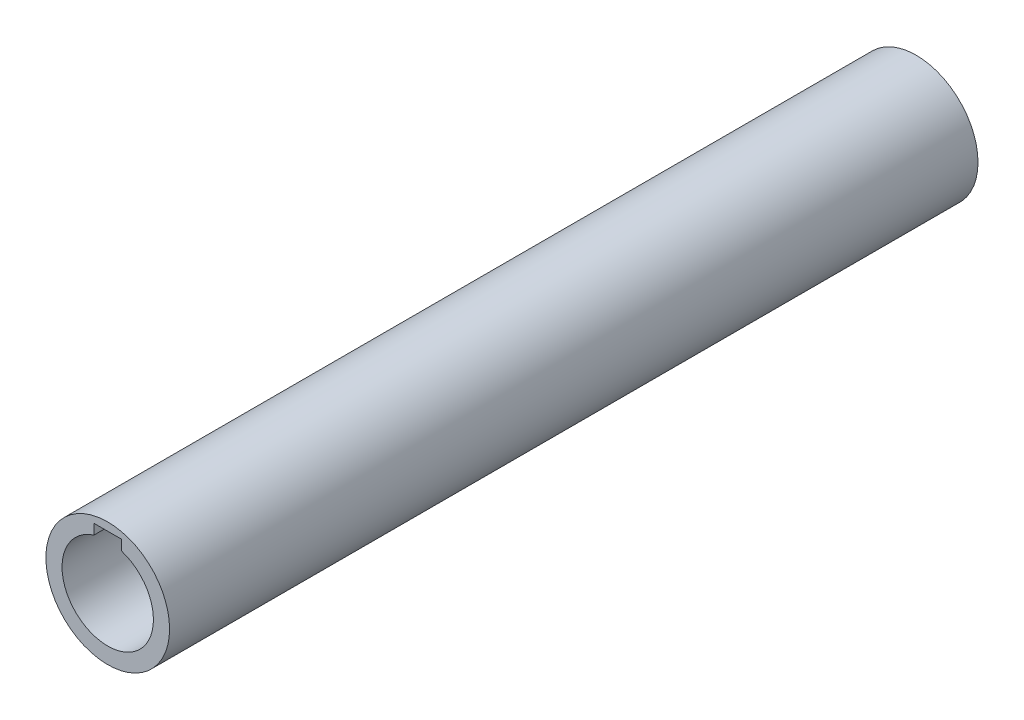
SolidWorks part; units mm, degrees
ref_plane "Front Plane" through (0, 0, 0) normal (0, 0, 1) x (1, 0, 0)
ref_plane "Top Plane" through (0, 0, 0) normal (0, 1, 0) x (1, 0, 0)
ref_plane "Right Plane" through (0, 0, 0) normal (1, 0, 0) x (0, 0, -1)
sketch "Sketch1" plane through (0, 0, 0) normal (0, 0, 1) x (1, 0, 0)
  circle A0 centre (0, 0) radius 38.25
  dimension "56.5" = 76.5
extrude "Boss-Extrude1" add sketch "Sketch1" along normal blind 250
sketch "Sketch3" plane through (0, 0, 250) normal (0, 0, 1) x (1, 0, 0)
  line L0 (-8.5, 26.9409) -> (-8.5, 33.25)
  line L3 (8.5, 33.25) -> (-8.5, 33.25)
  line L7 (8.5, 26.9409) -> (8.5, 33.25)
  arc A0 (-8.5, 26.9409) -> (8.5, 26.9409) centre (0, 0) ccw
  point P10 (0, 28.25)
  dimension "D1" = 56.5
  dimension "D2" = 33.25
  dimension "D3" = 17
extrude "Cut-Extrude2" cut sketch "Sketch3" against normal blind 50
mirror "Mirror1" about plane through (0, 0, 0) normal (0, 0, 1) of "Cut-Extrude2", "Boss-Extrude1"
sketch "Sketch4" plane through (0, 0, 0) normal (1, 0, 0) x (0, 0, -1)
  line L0 (0, 0) -> (486, 0) construction
  line L3 (0, 0) -> (-486, 0) construction
  dimension "D1" = 486
